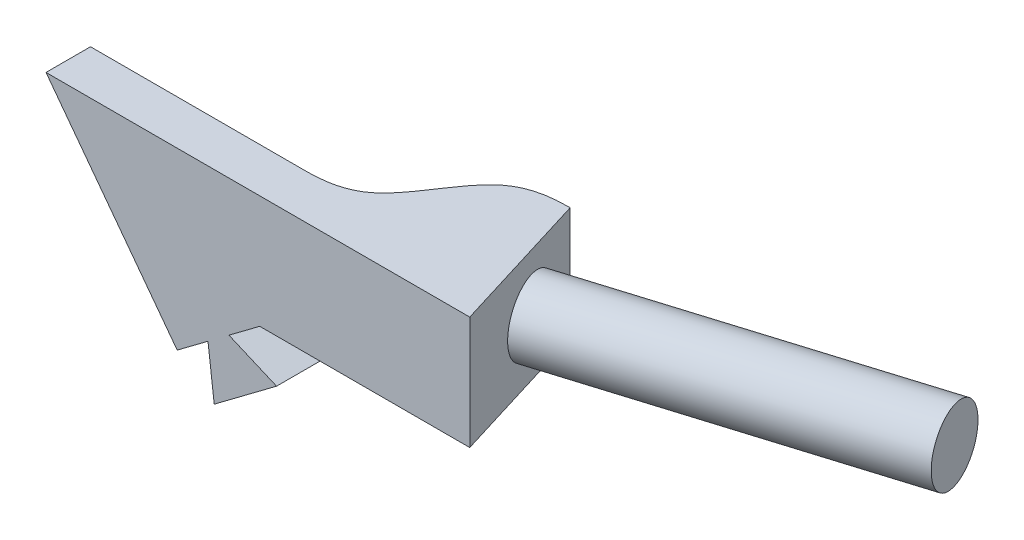
SolidWorks part; units mm, degrees
material "Custom Plastic"
ref_plane "X-Y Datum" through (0, 0, 0) normal (0, 0, 1) x (1, 0, 0)
ref_plane "X-Z Datum" through (0, 0, 0) normal (0, 1, 0) x (1, 0, 0)
ref_plane "Y-Z Datum" through (0, 0, 0) normal (1, 0, 0) x (0, 0, -1)
sketch "Sketch1" plane through (0, 0, 0) normal (0, 0, 1) x (1, 0, 0)
  line L1 (-38.1, -12.7) -> (38.1, -12.7)
  line L2 (-38.1, -12.7) -> (-38.1, 12.7)
  line L3 (-38.1, 12.7) -> (38.1, 12.7)
  line L4 (38.1, -12.7) -> (38.1, 12.7)
  line L5 (-38.1, -12.7) -> (38.1, 12.7) construction
  line L6 (-38.1, 12.7) -> (38.1, -12.7) construction
  point P0 (0, 0)
  dimension "D1" = 25.4
  dimension "D2" = 76.2
extrude "Boss-Extrude1" add sketch "Sketch1" along normal blind 12.7 and the other way blind 19.8782
sketch "Sketch2" plane through (0, -12.7, 0) normal (0, -1, 0) x (1, 0, 0)
  line L0 (28.0956, -19.8782) -> (38.1, 12.7)
  line L1 (-38.1, -19.8782) -> (38.1, -19.8782) construction
  line L2 (28.0956, -19.8782) -> (38.1, -19.8782)
  line L3 (38.1, -19.8782) -> (38.1, 12.7)
  line L4 (33.0978, -3.5891) -> (86.5661, -20.0085)
  line L5 (-38.1, 12.7) -> (38.1, 12.7) construction
  line L6 (-9.1056, 2.7) -> (-38.1, 2.7)
  line L7 (-38.1, -19.8782) -> (-38.1, 12.7) construction
  line L8 (30.3, -19.8782) -> (13.797, -19.8782)
  line L9 (-38.1, -19.8782) -> (-38.1, 2.7)
  line L10 (28.0956, -19.8782) -> (-38.1, -19.8782)
  spline S0 degree 3 poles (28.0956, -19.8782) (23.2625, -19.8782) (13.7597, -18.3883) (5.193, 1.2101) (-4.1851, 2.7) (-9.1056, 2.7) knots 0 0 0 0 0.311689 0.688311 1 1 1 1
  point P7 (33.0978, -3.5891)
  line M5 (38.1, -19.8782) -> (38.1, 12.7)
  line M8 (-38.1, -19.8782) -> (38.1, -19.8782)
  dimension "D1" = 17.071
  dimension "D2" = 28.9944
  dimension "D3" = 10
  dimension "D4" = 3.81
  dimension "D5" = 3.81
  dimension "D6" = 12.7
  dimension "D7" = 12.7
extrude "Cut-Extrude1" cut sketch "Sketch2" against normal through all contours L4 L0 M8 M5 | L0 L4 L3 | L10 L9 L6 S0
sketch "Sketch4" plane through (31.2528, 0, -9.5973) normal (0.9559, 0, -0.2936) x (-0.2936, 0, -0.9559)
  line L1 (-23.325, -12.7) -> (-23.325, 12.7) construction
  circle A0 centre (-2.5307, 0) radius 7.9375
  dimension "D1" = 15.875
  dimension "D2" = 20.7943
extrude "Boss-Extrude2" add sketch "Sketch4" along normal blind 76.2
sketch "Sketch5" plane through (0, 0, 2.7) normal (0, 0, -1) x (-1, 0, 0)
  line L0 (38.1, -12.7) -> (57.1506, 12.7)
  line L1 (57.1506, 12.7) -> (38.1, 12.7)
  line L2 (0, 0) -> (72.4016, 0) construction
  line L3 (72.4016, 0) -> (-7.6416, 60.0343) construction
  line L4 (38.1, 12.7) -> (38.1, -12.7)
  line L5 (9.1056, -12.7) -> (27.6616, -26.6174)
  line L6 (27.6616, -26.6174) -> (38.1, -12.7)
  line L7 (38.1, -12.7) -> (9.1056, -12.7)
  line L8 (16.0308, -17.894) -> (5.3229, -22.4677)
  line L9 (5.3229, -22.4677) -> (19.3435, -32.9836)
  line L10 (19.3435, -32.9836) -> (20.7365, -21.4234)
  line L11 (12.3332, -27.7257) -> (18.3836, -19.6587) construction
  line L12 (16.0308, -17.894) -> (20.7365, -21.4234)
  dimension "D1" = 36.871
  dimension "D2" = 60
  dimension "D3" = 60
  dimension "D4" = 17.526
  dimension "D5" = 10.0838
extrude "Boss-Extrude3" add sketch "Sketch5" against normal up to surface (10 mm away) up to face at (0, 0, 12.7)
sketch "Sketch6" [suppressed] plane through (0, 0, 2.7) normal (0, 0, -1) x (-1, 0, 0)
  line L0 (0, 0) -> (115.4941, 0) construction
  line L1 (115.4941, 0) -> (-57.8809, -130.0354) construction
  line L2 (38.1, 12.7) -> (57.1506, -12.7)
  line L3 (57.1506, -12.7) -> (38.1, -12.7)
  line L4 (38.1, -12.7) -> (38.1, 12.7)
  line L5 (38.1, 12.7) -> (27.6616, 26.6174)
  line L6 (27.6616, 26.6174) -> (9.1056, 12.7)
  line L7 (9.1056, 12.7) -> (38.1, 12.7) construction
  line L8 (9.1056, 12.7) -> (38.1, 12.7)
  line L9 (16.0308, 17.894) -> (5.3229, 22.4677)
  line L10 (5.3229, 22.4677) -> (19.3435, 32.9836)
  line L11 (19.3435, 32.9836) -> (20.7365, 21.4234)
  line L12 (12.3332, 27.7257) -> (18.3836, 19.6587) construction
  line L13 (16.0308, 17.894) -> (20.7365, 21.4234)
  line M5 (38.1, -12.7) -> (38.1, 12.7)
  line M6 (38.1, 12.7) -> (9.1056, 12.7)
  dimension "D1" = 36.871
  dimension "D2" = 60
  dimension "D3" = 60
  dimension "D4" = 10.0838
  dimension "D5" = 17.526
extrude "Boss-Extrude4" [suppressed] add sketch "Sketch6" against normal up to surface (10 mm away) contours L3 L2 M5 | L5 L6 M6 | L13 L11 L10 L9
